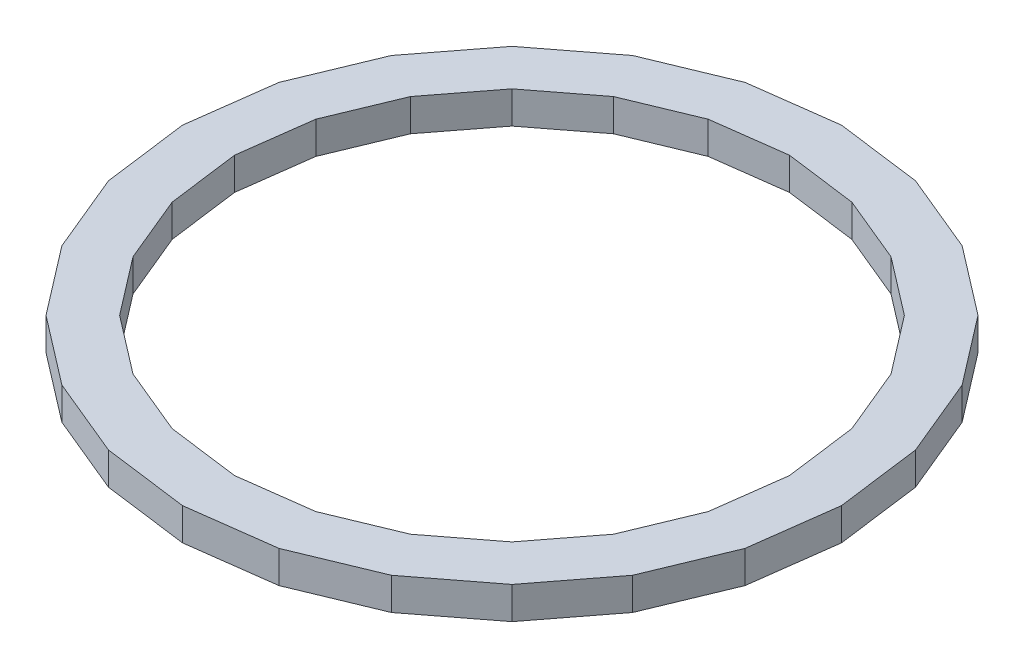
SolidWorks part; units mm, degrees
ref_plane "Front Plane" through (0, 0, 0) normal (0, 0, 1) x (1, 0, 0)
ref_plane "Top Plane" through (0, 0, 0) normal (0, 1, 0) x (1, 0, 0)
ref_plane "Right Plane" through (0, 0, 0) normal (1, 0, 0) x (0, 0, -1)
sketch "Sketch2" plane through (0, 0, 0) normal (0, 1, 0) x (1, 0, 0)
  line L0 (0, 0) -> (-163.8539, 0) construction
  line L1 (-194.597, 0) -> (-187.9662, -50.3654)
  line L2 (-187.9662, -50.3654) -> (-168.5259, -97.2985)
  line L3 (-168.5259, -97.2985) -> (-137.6008, -137.6008)
  line L4 (-137.6008, -137.6008) -> (-97.2985, -168.5259)
  line L5 (-97.2985, -168.5259) -> (-50.3654, -187.9662)
  line L6 (-50.3654, -187.9662) -> (0, -194.597)
  line L7 (0, -194.597) -> (50.3654, -187.9662)
  line L8 (50.3654, -187.9662) -> (97.2985, -168.5259)
  line L9 (97.2985, -168.5259) -> (137.6008, -137.6008)
  line L10 (137.6008, -137.6008) -> (168.5259, -97.2985)
  line L11 (168.5259, -97.2985) -> (187.9662, -50.3654)
  line L12 (187.9662, -50.3654) -> (194.597, 0)
  line L13 (194.597, 0) -> (187.9662, 50.3654)
  line L14 (187.9662, 50.3654) -> (168.5259, 97.2985)
  line L15 (168.5259, 97.2985) -> (137.6008, 137.6008)
  line L16 (137.6008, 137.6008) -> (97.2985, 168.5259)
  line L17 (97.2985, 168.5259) -> (50.3654, 187.9662)
  line L18 (50.3654, 187.9662) -> (0, 194.597)
  line L19 (0, 194.597) -> (-50.3654, 187.9662)
  line L20 (-50.3654, 187.9662) -> (-97.2985, 168.5259)
  line L21 (-97.2985, 168.5259) -> (-137.6008, 137.6008)
  line L22 (-137.6008, 137.6008) -> (-168.5259, 97.2985)
  line L23 (-168.5259, 97.2985) -> (-187.9662, 50.3654)
  line L24 (-187.9662, 50.3654) -> (-194.597, 0)
  line L25 (-163.8539, 0) -> (-158.2708, -42.4085)
  line L26 (-158.2708, -42.4085) -> (-141.9017, -81.927)
  line L27 (-141.9017, -81.927) -> (-115.8622, -115.8622)
  line L28 (-115.8622, -115.8622) -> (-81.927, -141.9017)
  line L29 (-81.927, -141.9017) -> (-42.4085, -158.2708)
  line L30 (-42.4085, -158.2708) -> (0, -163.8539)
  line L31 (0, -163.8539) -> (42.4085, -158.2708)
  line L32 (42.4085, -158.2708) -> (81.927, -141.9017)
  line L33 (81.927, -141.9017) -> (115.8622, -115.8622)
  line L34 (115.8622, -115.8622) -> (141.9017, -81.927)
  line L35 (141.9017, -81.927) -> (158.2708, -42.4085)
  line L36 (158.2708, -42.4085) -> (163.8539, 0)
  line L37 (163.8539, 0) -> (158.2708, 42.4085)
  line L38 (158.2708, 42.4085) -> (141.9017, 81.927)
  line L39 (141.9017, 81.927) -> (115.8622, 115.8622)
  line L40 (115.8622, 115.8622) -> (81.927, 141.9017)
  line L41 (81.927, 141.9017) -> (42.4085, 158.2708)
  line L42 (42.4085, 158.2708) -> (0, 163.8539)
  line L43 (0, 163.8539) -> (-42.4085, 158.2708)
  line L44 (-42.4085, 158.2708) -> (-81.927, 141.9017)
  line L45 (-81.927, 141.9017) -> (-115.8622, 115.8622)
  line L46 (-115.8622, 115.8622) -> (-141.9017, 81.927)
  line L47 (-141.9017, 81.927) -> (-158.2708, 42.4085)
  line L48 (-158.2708, 42.4085) -> (-163.8539, 0)
  line L49 (-194.597, 0) -> (-163.8539, 0) construction
  circle A0 centre (0, 0) radius 192.9322 construction
  circle A1 centre (0, 0) radius 162.4522 construction
  dimension "D1" = 50.8
  dimension "D2" = 30.48
extrude "Boss-Extrude2" add sketch "Sketch2" along normal blind 19.05
